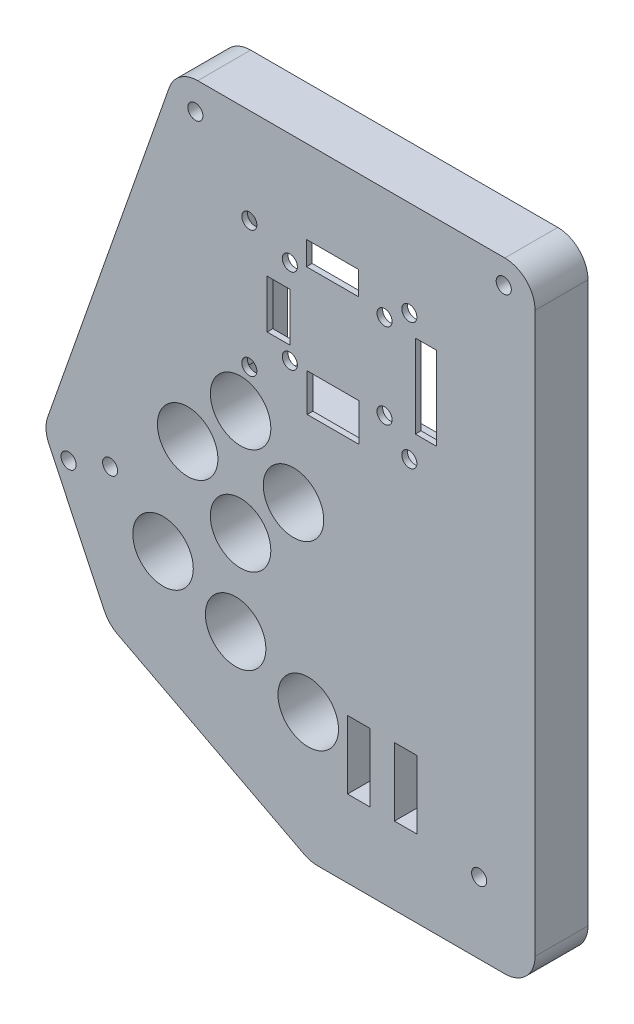
SolidWorks part; units mm, degrees
ref_plane "Front Plane" through (0, 0, 0) normal (0, 0, 1) x (1, 0, 0)
ref_plane "Top Plane" through (0, 0, 0) normal (0, 1, 0) x (1, 0, 0)
ref_plane "Right Plane" through (0, 0, 0) normal (1, 0, 0) x (0, 0, -1)
sketch "Sketch1" plane through (0, 0, 0) normal (0, 0, 1) x (1, 0, 0)
  line L6 (-20.066, -57.15) -> (46.99, -57.15) construction
  line L7 (-12.446, -73.152) -> (46.99, -73.152) construction
  line L8 (-3.3141, 6.35) -> (48.26, 6.35)
  line L9 (53.34, 1.27) -> (53.34, -92.71)
  line L10 (48.26, -97.79) -> (16.847, -97.79)
  line L16 (-8.1072, 2.9529) -> (-28.5162, -55.1739)
  line L18 (-20.066, -57.15) -> (-29.21, -57.15) construction
  line L26 (0, 0) -> (46.99, 0) construction
  line L27 (46.99, 0) -> (46.99, -88.9) construction
  line L28 (46.99, -88.9) -> (17.78, -88.9) construction
  line L29 (17.78, -88.9) -> (-12.446, -73.152) construction
  line L30 (-12.446, -73.152) -> (-20.066, -57.15) construction
  line L31 (-20.066, -57.15) -> (0, 0) construction
  line L32 (46.99, -57.15) -> (46.99, -88.9) construction
  line L33 (17.78, -88.9) -> (15.603, -97.79) construction
  line L34 (-12.446, -73.152) -> (-17.9301, -78.4424) construction
  line L35 (14.4997, -97.2152) -> (-16.7505, -80.9336)
  line L36 (-28.3096, -59.0409) -> (-18.9898, -78.6124)
  arc A0 (53.34, -92.71) -> (48.26, -97.79) centre (48.26, -92.71) cw
  arc A1 (48.26, 6.35) -> (53.34, 1.27) centre (48.26, 1.27) cw
  arc A2 (-8.1072, 2.9529) -> (-3.3141, 6.35) centre (-3.3141, 1.27) cw
  arc A3 (14.4997, -97.2152) -> (16.847, -97.79) centre (16.847, -92.71) ccw
  arc A4 (-16.7505, -80.9336) -> (-18.9898, -78.6124) centre (-14.4033, -76.4284) cw
  arc A5 (-28.5162, -55.1739) -> (-28.3096, -59.0409) centre (-23.723, -56.8568) ccw
  point P16 (53.34, -97.79)
  point P20 (53.34, 6.35)
  dimension "D8" = 5.08
  dimension "D9" = 5.08
  dimension "D1" = 88.9
  dimension "D2" = 29.21
  dimension "D3" = 59.436
  dimension "D4" = 67.056
  dimension "D5" = 104.14
  dimension "D6" = 82.55
  dimension "D7" = 46.99
  dimension "D13" = 103.76
  dimension "D17" = 108.51
extrude "Boss-Extrude1" add sketch "Sketch1" along normal blind 8.89
sketch "Sketch3" plane through (0, 0, 8.89) normal (0, 0, 1) x (1, 0, 0)
  line L6 (-20.066, -57.15) -> (46.99, -57.15) construction
  line L7 (-12.446, -73.152) -> (46.99, -73.152) construction
  line L8 (0, 0) -> (46.99, 0) construction
  line L9 (46.99, 0) -> (46.99, -88.9) construction
  line L10 (46.99, -88.9) -> (17.78, -88.9) construction
  line L11 (17.78, -88.9) -> (-12.446, -73.152) construction
  line L12 (-12.446, -73.152) -> (-20.066, -57.15) construction
  line L13 (-20.066, -57.15) -> (0, 0) construction
  line L14 (3.8784, -55.88) -> (3.8784, -38.1) construction
  circle A0 centre (3.8784, -38.1) radius 5.08
  circle A1 centre (-5.0116, -46.99) radius 5.08
  circle A2 centre (3.8784, -55.88) radius 5.08
  circle A3 centre (12.7684, -46.99) radius 5.08
  circle A4 centre (-9.144, -65.024) radius 5.08
  circle A5 centre (3.048, -70.612) radius 5.08
  circle A6 centre (15.24, -76.2) radius 5.08
  dimension "D7" = 10.16
  dimension "D1" = 43.1116
  dimension "D2" = 8.89
  dimension "D3" = 8.89
  dimension "D4" = 46.99
  dimension "D5" = 8.89
  dimension "D6" = 8.89
  dimension "D8" = 12.192
  dimension "D9" = 5.588
  dimension "D10" = 5.588
  dimension "D11" = 12.192
  dimension "D12" = 43.942
  dimension "D13" = 70.612
sketch "Sketch4" plane through (0, 0, 0) normal (0, 0, 1) x (1, 0, 0)
  line L0 (2.8795, -3.175) -> (2.8795, -33.655)
  line L6 (2.8795, -3.175) -> (37.1695, -3.175)
  line L9 (37.1695, -3.175) -> (37.1695, -33.655)
  line L48 (37.1695, -33.655) -> (2.8795, -33.655)
  line L50 (46.99, 0) -> (46.99, -88.9) construction
  dimension "D1" = 9.8205
  dimension "D2" = 34.29
  dimension "D3" = 30.48
sketch "Sketch9" plane through (0, 0, 0) normal (0, 0, -1) x (-1, 0, 0)
  line L0 (-46.99, 0) -> (-46.99, -88.9) construction
  line L7 (-36.7885, -35.5217) -> (-36.7885, -40.4326) construction
  line L8 (-53.34, -92.71) -> (-53.34, 1.27) construction
  line L9 (-48.26, 6.35) -> (3.3141, 6.35) construction
  line L10 (3.3141, 6.35) -> (-48.26, 6.35) construction
  line L11 (-53.34, 1.27) -> (-53.34, -92.71) construction
  line L25 (-3.2605, -20.3148) -> (-36.7885, -20.3148) construction
  line L26 (-33.4865, -32.221) -> (-29.908, -32.221) construction
  line L27 (-33.4865, -33.0148) -> (-33.4865, -29.5416) construction
  line L28 (-4.0809, -8.4085) -> (-4.0809, -11.8133) construction
  line L29 (-4.0809, -8.4085) -> (-9.1758, -8.4085) construction
  line L30 (-5.0385, -17.1398) -> (-5.005, -17.1398) construction
  line L31 (-5.0385, -7.6148) -> (-5.0652, -7.6148) construction
  line L32 (-8.3409, -24.3788) -> (-8.3409, -16.2508)
  line L33 (-15.0648, -33.0148) -> (-23.8027, -33.0148)
  line L34 (-36.7885, -26.7831) -> (-33.2325, -26.7831)
  line L35 (-36.7885, -12.8131) -> (-36.7885, -26.7831)
  line L36 (-14.9445, -7.6148) -> (-23.6757, -7.6148)
  line L37 (-23.6757, -7.6148) -> (-23.6757, -11.5835)
  line L38 (-15.0648, -33.0148) -> (-15.0648, -26.6648)
  line L39 (-23.8027, -26.6648) -> (-23.8027, -33.0148)
  line L40 (-12.1509, -24.3788) -> (-8.3409, -24.3788)
  line L41 (-8.3409, -16.2508) -> (-12.1509, -16.2508)
  line L42 (-33.2325, -12.8131) -> (-36.7885, -12.8131)
  line L43 (-12.1509, -16.2508) -> (-12.1509, -24.3788)
  line L44 (-14.9445, -11.5835) -> (-23.6757, -11.5835)
  line L45 (-14.9445, -7.6148) -> (-14.9445, -11.5835)
  line L46 (-23.8027, -26.6648) -> (-20.9135, -26.6648)
  line L47 (-15.0648, -26.6648) -> (-20.9135, -26.6648)
  line L48 (-33.2325, -12.8131) -> (-33.2325, -26.7831)
  circle A8 centre (-5.3484, -30.9535) radius 1.2675
  circle A9 centre (-32.219, -9.6761) radius 1.2675
  circle A10 centre (-12.1505, -12.3773) radius 1.2675
  circle A11 centre (-12.1505, -26.6648) radius 1.2675
  circle A12 centre (-28.0572, -12.3773) radius 1.2675
  circle A13 centre (-5.3484, -9.6761) radius 1.2675
  circle A14 centre (-32.219, -30.9535) radius 1.2675
  circle A15 centre (-28.0572, -26.6648) radius 1.2675
  dimension "D1" = 2.535
  dimension "D2" = 10.2015
  dimension "D3" = 16.5515
  dimension "D4" = 19.1631
  dimension "D5" = 13.97
  dimension "D6" = 16.0261
  dimension "D7" = 21.121
extrude "Cut-Extrude6" cut sketch "Sketch9" against normal through all both and the other way through all
extrude "Cut-Extrude7" cut sketch "Sketch4" along normal blind 7.9375 and the other way through all
extrude "Cut-Extrude8" cut sketch "Sketch3" against normal through all both and the other way through all
sketch "Sketch12" plane through (0, 0, 0) normal (0, 0, -1) x (-1, 0, 0)
  line L0 (-48.26, 6.35) -> (3.3141, 6.35) construction
  line L1 (-53.34, -92.71) -> (-53.34, 1.27) construction
  line L2 (8.1072, 2.9529) -> (28.5162, -55.1739) construction
  line L3 (28.3096, -59.0409) -> (18.9898, -78.6124) construction
  circle A0 centre (-48.0822, 2.286) radius 1.27
  circle A1 centre (3.7187, 1.651) radius 1.27
  circle A2 centre (25.0123, -59.762) radius 1.27
  dimension "D1" = 2.54
  dimension "D2" = 4.064
  dimension "D3" = 5.2578
  dimension "D4" = 4.699
  dimension "D5" = 4.572
  dimension "D6" = 4.826
  dimension "D7" = 2.667
extrude "Cut-Extrude9" cut sketch "Sketch12" against normal through all both and the other way through all
sketch "Sketch15" plane through (0, 0, 0) normal (0, 0, -1) x (-1, 0, 0)
  line L0 (-37.465, -31.4407) -> (-43.942, -85.852) construction
  line L1 (20.066, -57.15) -> (18.034, -57.15) construction
  line L2 (20.066, -57.15) -> (-46.99, -57.15) construction
  circle A0 centre (18.034, -57.15) radius 1.27
  circle A1 centre (-43.942, -85.852) radius 1.27
  dimension "D1" = 2.54
  dimension "D2" = 2.032
  dimension "D3" = 54.7954
extrude "Cut-Extrude10" cut sketch "Sketch15" against normal through all both and the other way through all
sketch "Sketch16" plane through (0, 0, 0) normal (0, 0, -1) x (-1, 0, 0)
  line L0 (-21.844, -73.406) -> (-25.654, -73.406)
  line L1 (-21.844, -73.406) -> (-21.844, -84.836)
  line L2 (-21.844, -84.836) -> (-25.654, -84.836)
  line L3 (-25.654, -73.406) -> (-25.654, -84.836)
  line L4 (-29.718, -73.406) -> (-33.528, -73.406)
  line L5 (-29.718, -73.406) -> (-29.718, -84.836)
  line L6 (-29.718, -84.836) -> (-33.528, -84.836)
  line L7 (-33.528, -73.406) -> (-33.528, -84.836)
  line L8 (-46.99, 0) -> (-46.99, -88.9) construction
  line L9 (-46.99, -88.9) -> (-17.78, -88.9) construction
  point P10 (-31.623, -84.836)
  dimension "D1" = 11.43
  dimension "D2" = 3.81
  dimension "D3" = 4.064
  dimension "D4" = 11.43
  dimension "D5" = 3.81
  dimension "D6" = 13.462
  dimension "D7" = 4.064
  dimension "D8" = 4.064
extrude "Cut-Extrude11" cut sketch "Sketch16" against normal through all both and the other way through all
